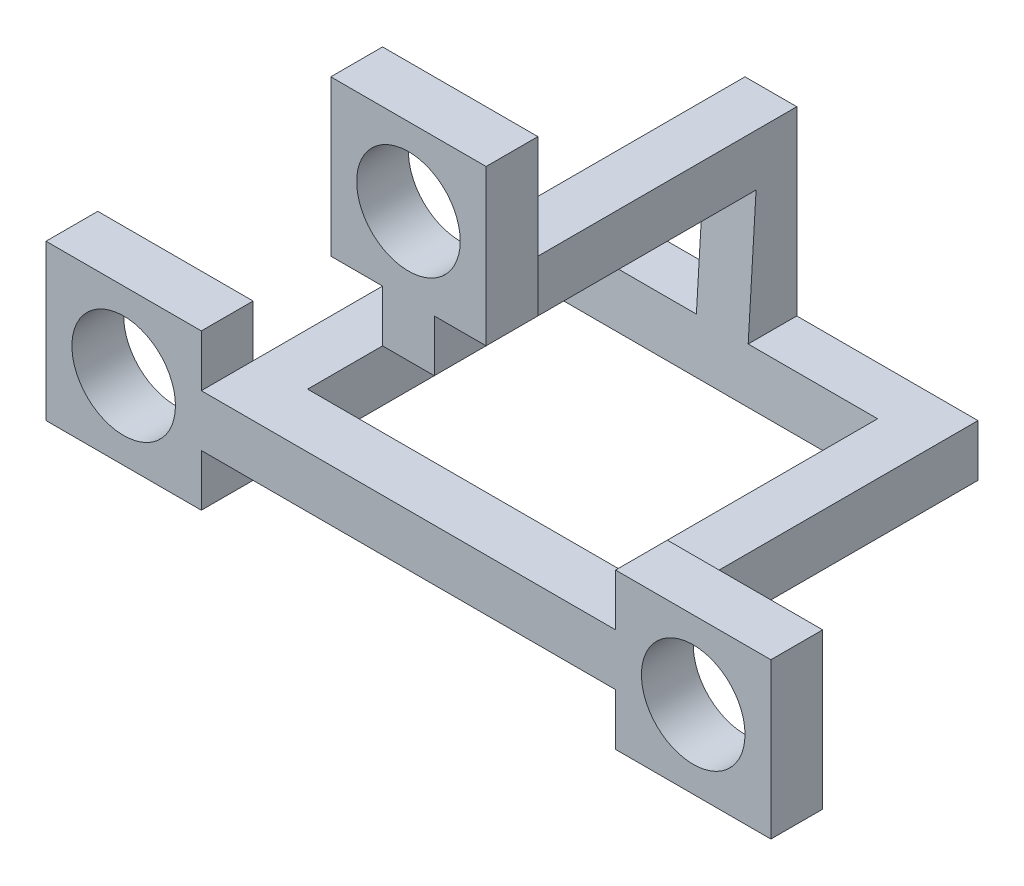
SolidWorks part; units mm, degrees
ref_plane "Front Plane" through (0, 0, 0) normal (0, 0, 1) x (1, 0, 0)
ref_plane "Top Plane" through (0, 0, 0) normal (0, 1, 0) x (1, 0, 0)
ref_plane "Right Plane" through (0, 0, 0) normal (1, 0, 0) x (0, 0, -1)
sketch "Sketch6" plane through (0, 0, 0) normal (0, 1, 0) x (1, 0, 0)
  line L0 (-14, 0) -> (14, 0)
  line L2 (-6, 12) -> (6, 12)
  line L5 (14, 0) -> (14, 2)
  line L6 (14, 2) -> (8, 2)
  line L7 (8, 2) -> (8, 14)
  line L8 (8, 14) -> (-8, 14)
  line L9 (-8, 14) -> (-8, 2)
  line L10 (-8, 2) -> (-14, 2)
  line L11 (-14, 2) -> (-14, 0)
  line L13 (-6, 4) -> (6, 4)
  line L14 (6, 4) -> (6, 12)
  line L15 (-6, 12) -> (-6, 4)
  point P1 (8, 8)
  point P15 (11.9556, 0)
  dimension "D1" = 2
  dimension "D2" = 2
  dimension "D3" = 12
  dimension "D4" = 6
  dimension "D5" = 2
  dimension "D6" = 2
  dimension "D7" = 2
  dimension "D8" = 10
  dimension "D9" = 6
  dimension "D10" = 6
  dimension "D11" = 2
extrude "Boss-Extrude5" add sketch "Sketch6" along normal mid plane 2
sketch "Sketch7" plane through (0, 0, -2) normal (0, 0, -1) x (-1, 0, 0)
  line L0 (14, 1) -> (14, -1) construction
  line L1 (8, 1) -> (14, 1)
  line L2 (8, 1) -> (8, 3)
  line L3 (8, 3) -> (14, 3)
  line L4 (14, 1) -> (14, 3)
  line L5 (8, -1) -> (14, -1)
  line L6 (8, -1) -> (8, -3)
  line L7 (8, -3) -> (14, -3)
  line L8 (14, -1) -> (14, -3)
  dimension "D1" = 2
  dimension "D2" = 2
extrude "Boss-Extrude6" add sketch "Sketch7" against normal up to surface (2 mm away) up to face at (0, 0, 0)
mirror "Mirror2" about plane through (0, 0, 0) normal (1, 0, 0) of "Boss-Extrude6"
ref_plane "Plane1" through (0, -0.2651, 0.0162) normal (0, 0.9981, -0.061) x (-1, 0, 0)
sketch "Sketch8" plane through (0, -0.2651, 0.0162) normal (0, 0.9981, -0.061) x (-1, 0, 0)
  line L1 (6, -12.0387) -> (-6, -12.0387)
  line L2 (6, -12.0387) -> (6, -2.0387)
  line L3 (6, -2.0387) -> (-6, -2.0387)
  line L4 (-6, -12.0387) -> (-6, -2.0387)
  dimension "D1" = 12
  dimension "D2" = 10
extrude "Cut-Extrude4" cut sketch "Sketch8" against normal mid plane 5
sketch "Sketch10" plane through (0, 0, 0) normal (1, 0, 0) x (0, 0, -1)
  line L9 (0, 3) -> (0, -3) construction
  line L10 (12.1223, 1) -> (12.4281, 6)
  line L11 (12, -1) -> (12.1223, 1) construction
  line L13 (12.4281, 6) -> (0, 6)
  line L14 (0, 6) -> (0, 14)
  line L15 (0, 14) -> (2, 14)
  line L16 (2, 14) -> (2, 8)
  line L17 (2, 8) -> (14, 8)
  line L18 (14, 8) -> (14, 1)
  line L19 (14, 1) -> (12.1223, 1)
  line L20 (14, 1) -> (2, 1) construction
  point P0 (12.7006, 10.0309)
  dimension "D1" = 2
  dimension "D2" = 2
  dimension "D3" = 6
  dimension "D4" = 5
extrude "Boss-Extrude7" add sketch "Sketch10" along normal mid plane 2
sketch "Sketch12" plane through (0, 0, -2) normal (0, 0, -1) x (-1, 0, 0)
  line L0 (-1, 8) -> (-1, 14) construction
  line L1 (-3, 14) -> (3, 14)
  line L2 (-3, 14) -> (-3, 8)
  line L3 (-3, 8) -> (3, 8)
  line L4 (3, 14) -> (3, 8)
  line L5 (1, 8) -> (1, 14) construction
  line L6 (-1, 14) -> (1, 14) construction
  dimension "D1" = 6
  dimension "D2" = 2
  dimension "D3" = 2
extrude "Boss-Extrude9" add sketch "Sketch12" against normal up to surface (2 mm away) up to face at (0, 10, 0)
sketch "Sketch13" plane through (0, 0, 0) normal (0, 0, 1) x (1, 0, 0)
  line L1 (-14, 3) -> (-14, -3) construction
  line L3 (-3, 14) -> (-3, 8) construction
  circle A0 centre (-11, 0) radius 2
  circle A1 centre (11, 0) radius 2
  circle A2 centre (0, 11) radius 2
  point P6 (-10.9751, -0.7401)
  point P10 (-14, 0)
  point P11 (2.2766, 12.6928)
  point P14 (-3, 11)
  dimension "D1" = 4
  dimension "D2" = 4
  dimension "D3" = 4
  dimension "D4" = 11
  dimension "D5" = 11
  dimension "D6" = 0
  dimension "D7" = 0
extrude "Cut-Extrude7" cut sketch "Sketch13" against normal through all
